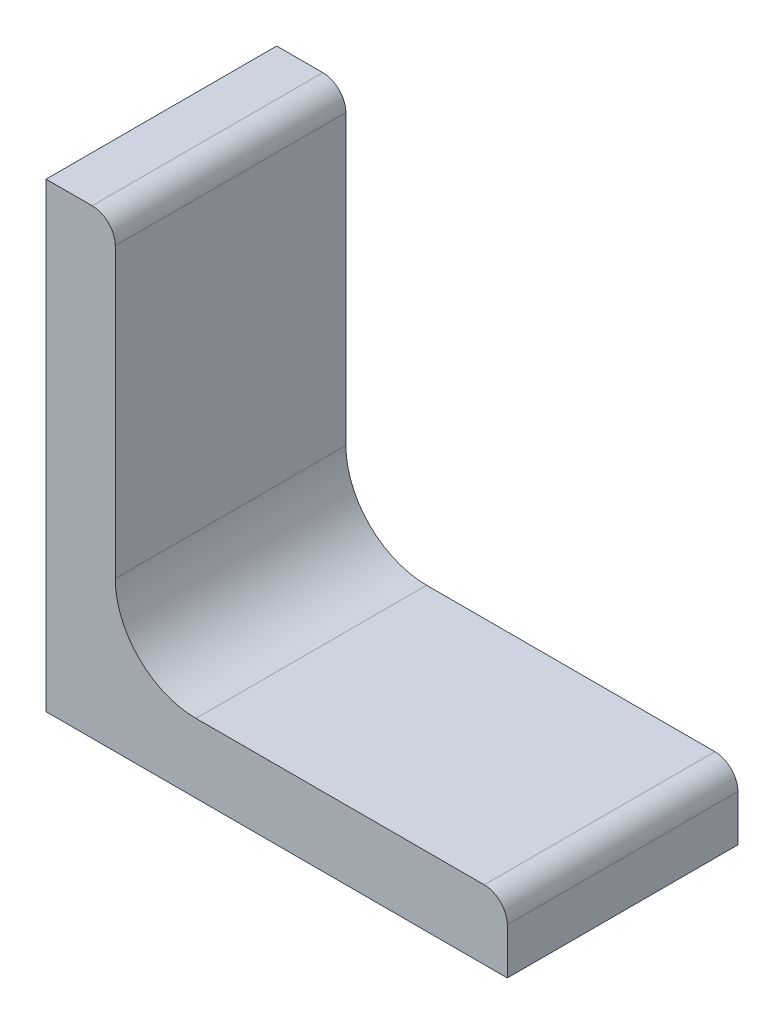
SolidWorks part; units mm, degrees
material "普通碳钢"
ref_plane "前视基准面" through (0, 0, 0) normal (0, 0, 1) x (1, 0, 0)
ref_plane "上视基准面" through (0, 0, 0) normal (0, 1, 0) x (1, 0, 0)
ref_plane "右视基准面" through (0, 0, 0) normal (1, 0, 0) x (0, 0, -1)
sketch "草图1" plane through (0, 0, 0) normal (0, 0, -1) x (-1, 0, 0)
  line L0 (0, 20) -> (0, 0)
  line L1 (0, 0) -> (-20, 0)
  line L2 (-20, 0) -> (-20, 3)
  line L3 (-20, 3) -> (-3, 3)
  line L4 (-3, 3) -> (-3, 20)
  line L5 (-3, 20) -> (0, 20)
  dimension "D1" = 20
  dimension "D2" = 3
extrude "凸台-拉伸1" add sketch "草图1" against normal blind 10
fillet "圆角1" radius 1 2 edges at (20, 3, 5) (3, 20, 5)
fillet "圆角2" radius 3.5 1 edges at (3, 3, 5)
